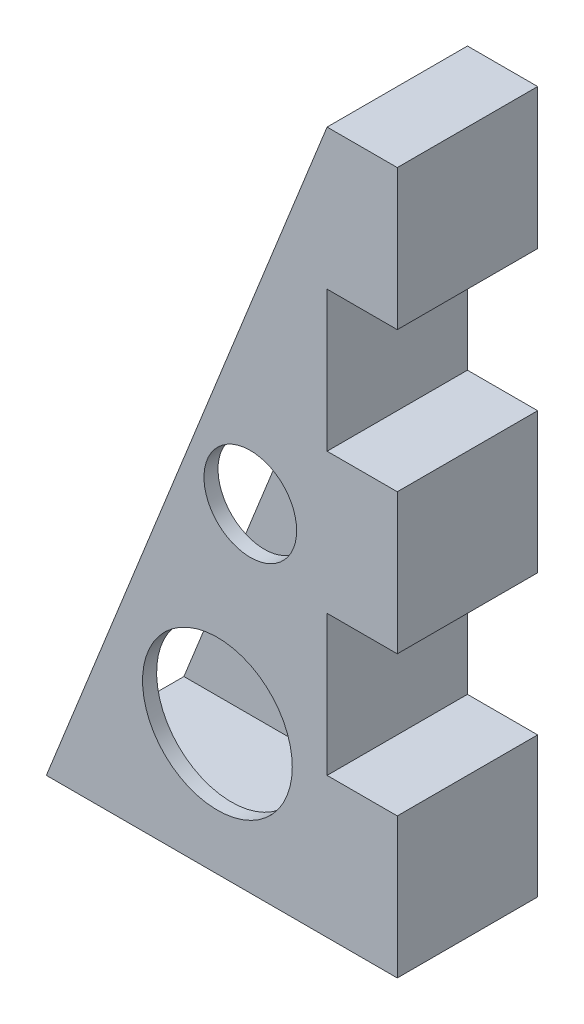
SolidWorks part; units mm, degrees
ref_plane "前视基准面" through (0, 0, 0) normal (0, 0, 1) x (1, 0, 0)
ref_plane "上视基准面" through (0, 0, 0) normal (0, 1, 0) x (1, 0, 0)
ref_plane "右视基准面" through (0, 0, 0) normal (1, 0, 0) x (0, 0, -1)
other "Configuration Table"
sketch "草图1" plane through (0, 0, 0) normal (0, 0, 1) x (1, 0, 0)
  line L0 (0, 0) -> (43.4148, 0)
  line L1 (43.4148, 0) -> (43.4148, 10)
  line L2 (43.4148, 10) -> (38.4148, 10)
  line L3 (38.4148, 10) -> (38.4148, 20)
  line L4 (38.4148, 20) -> (43.4148, 20)
  line L5 (43.4148, 20) -> (43.4148, 30)
  line L6 (43.4148, 30) -> (38.4148, 30)
  line L7 (38.4148, 30) -> (38.4148, 40)
  line L8 (38.4148, 40) -> (43.4148, 40)
  line L9 (43.4148, 40) -> (43.4148, 50)
  line L10 (43.4148, 50) -> (38.4148, 50)
  line L11 (38.4148, 50) -> (18.4148, 0)
  line L12 (18.4148, 0) -> (0, 0)
  point P16 (41.1383, 0)
  dimension "D1" = 10
  dimension "D2" = 10
  dimension "D3" = 10
  dimension "D4" = 5
  dimension "D5" = 10
  dimension "D6" = 25
  dimension "D7" = 50
  dimension "D8" = 43.4148
extrude "凸台-拉伸1" add sketch "草图1" against normal blind 10 contours L10 L11 L0 L1 L2 L3 L4 L5 L6 L7 L8 L9
sketch "草图3" plane through (0, 0, 0) normal (1, 0, 0) x (0, 0, -1)
  line L7 (5, 0) -> (5, 50) construction
  line L8 (10, 0) -> (0, 0) construction
  line L9 (10, 50) -> (0, 50) construction
  line L10 (1, 50) -> (9, 50)
  line L11 (9, 50) -> (9, 2)
  line L13 (1, 50) -> (1, 2)
  line L15 (9, 2) -> (1, 2)
  dimension "D1" = 4
  dimension "D2" = 2
extrude "切除-拉伸4" cut sketch "草图3" along normal offset from surface (86.4148 mm away) 2
sketch "草图4" plane through (0, 0, 0) normal (0, 0, 1) x (1, 0, 0)
  circle A0 centre (30.6014, 9.2776) radius 5.3332
  circle A2 centre (32.9447, 24.0137) radius 3.3003
extrude "切除-拉伸6" cut sketch "草图4" against normal through all contours A0 | A2
sketch "草图5" plane through (0, 0, 0) normal (0, 0, 1) x (1, 0, 0)
  line L0 (7.7446, 51.8851) -> (7.7446, -1.1376) construction
ref_plane "基准面9" through (49.6037, 0, 0) normal (1, 0, 0) x (0, 0, -1)
